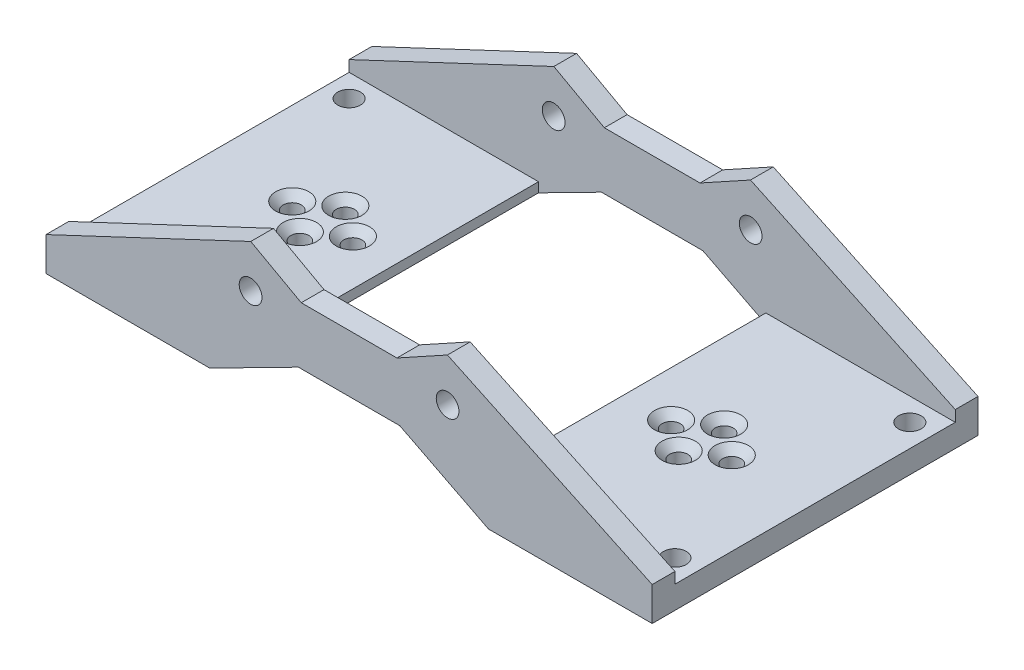
SolidWorks part; units mm, degrees
other "Markup1"
sketch "Sketch62" plane through (-128.5, -128.5, 146.8) normal (-0.0672, -0.6619, 0.7466) x (0.996, 0, 0.0896)
other "Markup2"
sketch "Sketch87" plane through (-128.5, 200.1498, -230) normal (-0.7911, 0.6051, -0.0891) x (-0.112, 0, 0.9937)
ref_plane "Front" through (0, 0, 0) normal (0, 0, 1) x (1, 0, 0)
ref_plane "Top" through (0, 0, 0) normal (0, 1, 0) x (1, 0, 0)
ref_plane "Right" through (0, 0, 0) normal (1, 0, 0) x (0, 0, -1)
sketch "Sketch1" plane through (0, 0, 0) normal (0, 0, 1) x (1, 0, 0)
  line L0 (-50.5181, 87.5) -> (0, 0) construction
  line L1 (101.0363, 0) -> (50.5181, 87.5)
  line L2 (50.5181, 87.5) -> (-50.5181, 87.5)
  line L3 (-50.5181, 87.5) -> (-101.0363, 0)
  line L4 (-101.0363, 0) -> (-50.5181, -87.5)
  line L5 (-50.5181, -87.5) -> (50.5181, -87.5)
  line L6 (50.5181, -87.5) -> (101.0363, 0)
  line L7 (0, 128.5) -> (-111.2843, 64.25) construction
  line L8 (-111.2843, 64.25) -> (-111.2843, -64.25) construction
  line L9 (-111.2843, -64.25) -> (0, -128.5) construction
  line L10 (0, -128.5) -> (111.2843, -64.25) construction
  line L11 (111.2843, -64.25) -> (111.2843, 64.25) construction
  line L12 (111.2843, 64.25) -> (0, 128.5) construction
  line L13 (0, 0) -> (50.5181, 87.5) construction
  line L14 (0, 0) -> (0, 200.1498) construction
  line L15 (-25, 93.5) -> (-25, 88.55) construction
  line L16 (-27.5, 91.1) -> (-22.5, 91.1)
  line L17 (-27.5, 91.1) -> (-27.5, 87.5)
  line L18 (-27.5, 87.5) -> (-22.5, 87.5)
  line L19 (-22.5, 91.1) -> (-22.5, 87.5)
  line L20 (-31, 93.5) -> (-19, 93.5)
  line L21 (-31, 93.5) -> (-31, 88.55)
  line L22 (-31, 88.55) -> (-19, 88.55)
  line L23 (-19, 93.5) -> (-19, 88.55)
  line L24 (48.2087, 83.5) -> (-48.2087, 83.5)
  line L25 (-48.2087, 83.5) -> (-96.4175, 0)
  line L26 (-96.4175, 0) -> (-48.2087, -83.5)
  line L27 (-48.2087, -83.5) -> (48.2087, -83.5)
  line L28 (48.2087, -83.5) -> (96.4175, 0)
  line L29 (96.4175, 0) -> (48.2087, 83.5)
  line L30 (-13, 105) -> (-13, 90) construction
  line L31 (-13, 105) -> (-0.0096, 97.5) construction
  line L32 (-11.2098, 101.4229) -> (-21.0467, 96.5)
  line L33 (-11.2098, 101.4229) -> (-7.6328, 103.2131)
  line L34 (-7.6328, 103.2131) -> (-9.4229, 106.7902)
  line L35 (-10.7973, 108.3389) -> (-23.318, 116.5991)
  line L36 (-22, 93.5) -> (-20, 93.5)
  line L37 (-22, 93.5) -> (-22, 91.5)
  line L38 (-22, 91.5) -> (-20, 91.5)
  line L39 (-20, 93.5) -> (-20, 91.5)
  line L40 (-30, 93.5) -> (-28, 93.5)
  line L41 (-30, 93.5) -> (-30, 91.5)
  line L42 (-30, 91.5) -> (-28, 91.5)
  line L43 (-28, 93.5) -> (-28, 91.5)
  line L44 (-26, 93.5) -> (-24, 93.5)
  line L45 (-26, 93.5) -> (-26, 91.5)
  line L46 (-26, 91.5) -> (-24, 91.5)
  line L47 (-24, 93.5) -> (-24, 91.5)
  line L48 (-10.7973, 108.3389) -> (-7.4584, 106.1361)
  line L49 (-7.4584, 106.1361) -> (-9.6611, 102.7973)
  line L50 (-12.9761, 110.6824) -> (-40, 97.9593)
  line L51 (-40, 97.9593) -> (-40, 93.5)
  line L52 (-40, 93.5) -> (-31, 93.5)
  line L53 (-14.7902, 108.5771) -> (-28.2041, 101.8639)
  line L54 (-40, 93.5) -> (-40, 82)
  line L55 (-40, 82) -> (-34, 72.5)
  line L56 (-34, 93.5) -> (-34, 82)
  line L57 (-34, 82) -> (-31.7895, 78.5)
  line L58 (-31.7895, 78.5) -> (-10.583, 78.5)
  line L59 (-34, 72.5) -> (-10.583, 72.5)
  line L60 (-19, 93.5) -> (-18.3926, 93.5)
  line L61 (-18.3926, 93.5) -> (-6.6883, 99.4573)
  line L62 (-6.6883, 99.4573) -> (0, 99.4573)
  line L63 (-12.9761, 110.6824) -> (-6.312, 107.0092)
  line L64 (-6.312, 107.0092) -> (0, 107.0092)
  line L65 (-6.4952, 79.25) -> (0, 75.5) construction
  line L66 (0, 75.5) -> (-8.2568, 75.5) construction
  line L67 (-9.5263, 81) -> (9.5263, 81)
  line L68 (-9.5263, 70) -> (9.5263, 70)
  line L69 (-37, 86.5) -> (-37, 97.0992) construction
  line L70 (-38.5, 93.5) -> (-35.5, 93.5) construction
  line L71 (-38.5, 93.5) -> (-38.5, 86.5) construction
  line L72 (-38.5, 86.5) -> (-35.5, 86.5) construction
  line L73 (-35.5, 93.5) -> (-35.5, 86.5) construction
  circle A0 centre (0, 0) radius 87.5 construction
  circle A1 centre (0, 0) radius 128.5 construction
  circle A2 centre (0, 128.5) radius 21 construction
  circle A3 centre (0, 128.5) radius 37.5 construction
  circle A4 centre (-13, 105) radius 1.5
  circle A5 centre (-13, 105) radius 15 construction
  circle A6 centre (-13, 105) radius 4
  arc A7 (-47.2558, 123.0415) -> (-49.9693, 122.4426) centre (-48.6061, 122.7128) ccw
  arc A8 (-47.2558, 123.0415) -> (-16.059, 109.9939) centre (-26.8516, 128.0083) ccw
  arc A9 (-49.9693, 122.4426) -> (-11.6134, 101.248) centre (-21.6463, 128.3951) ccw
  arc A10 (-14.5035, 143.6871) -> (-16.3789, 145.7376) centre (-15.4633, 144.6921) ccw
  arc A11 (-14.5035, 143.6871) -> (-10.2047, 110.1461) centre (0, 128.5) ccw
  arc A12 (-16.3789, 145.7376) -> (-15.556, 101.9232) centre (2.9376, 124.1854) ccw
  circle A13 centre (0, 75.5) radius 5
  circle A14 centre (0, 75.5) radius 3
  arc A15 (-9.5263, 81) -> (-9.5263, 70) centre (0, 75.5) ccw
  circle A16 centre (-6.4952, 79.25) radius 1.25 construction
  circle A18 centre (-6.4952, 79.25) radius 2.3 construction
  circle A19 centre (-6.4952, 71.75) radius 2.3 construction
  circle A20 centre (-6.4952, 71.75) radius 1.25 construction
  arc A21 (9.5263, 70) -> (9.5263, 81) centre (0, 75.5) ccw
  circle A22 centre (6.4952, 71.75) radius 1.25 construction
  circle A23 centre (6.4952, 79.25) radius 1.25 construction
  circle A24 centre (0, 0) radius 40.25 construction
  circle A25 centre (-8, 75.5) radius 1.75
  circle A26 centre (8, 75.5) radius 1.75
  point P29 (-25, 91.1)
  point P30 (-25, 93.5)
  point P73 (-25, 91.5)
  point P74 (-29, 91.5)
  point P75 (-21, 91.5)
  dimension "D1" = 175
  dimension "D2" = 257
  dimension "D3" = 42
  dimension "D4" = 75
  dimension "D5" = 3
  dimension "D14" = 30
  dimension "D15" = 8
  dimension "D26" = 6
  dimension "D27" = 10
  dimension "D28" = 22
  dimension "D30" = 2.5
  dimension "D31" = 4.6
  dimension "D40" = 80.5
  dimension "D41" = 3.5
  dimension "D6" = 3.6
  dimension "D7" = 6
  dimension "D8" = 12
  dimension "D9" = 5
  dimension "D10" = 4.95
  dimension "D11" = 25
  dimension "D13" = 60
  dimension "D16" = 15
  dimension "D17" = 2
  dimension "D18" = 8
  dimension "D19" = 2
  dimension "D20" = 5
  dimension "D21" = 13
  dimension "D22" = 17.5
  dimension "D23" = 60
  dimension "D24" = 19
  dimension "D25" = 40
  dimension "D29" = 7.5
  dimension "D32" = 30
  dimension "D33" = 11
  dimension "D34" = 8
  dimension "D35" = 6
  dimension "D36" = 3
  dimension "D37" = 7
  dimension "D38" = 11.5
  dimension "D39" = 6
  dimension "D42" = 16
  dimension "D12" = 4
sketch "Sketch2" plane through (0, 0, 0) normal (0, 0, 1) x (1, 0, 0)
  line L0 (-27.5, 91.1) -> (-27.5, 87.5) construction
  line L1 (-27.5, 87.5) -> (-22.5, 87.5) construction
  line L2 (-22.5, 91.1) -> (-22.5, 87.5) construction
  line L3 (-27.5, 91.1) -> (-22.5, 91.1) construction
  line L8 (-27.5, 91.1) -> (-27.5, 87.5)
  line L9 (-27.5, 87.5) -> (-22.5, 87.5)
  line L10 (-22.5, 91.1) -> (-22.5, 87.5)
  line L11 (-27.5, 91.1) -> (-22.5, 91.1)
sketch "Sketch3" plane through (0, 0, 0) normal (0, 0, 1) x (1, 0, 0)
  line L0 (-31, 93.5) -> (-19, 93.5) construction
  line L1 (-19, 93.5) -> (-19, 88.55) construction
  line L2 (-31, 88.55) -> (-19, 88.55) construction
  line L3 (-31, 93.5) -> (-31, 88.55) construction
  line L4 (-31, 93.5) -> (-19, 93.5)
  line L5 (-19, 93.5) -> (-19, 88.55)
  line L6 (-31, 88.55) -> (-19, 88.55)
  line L7 (-31, 93.5) -> (-31, 88.55)
ref_plane "Plane3" through (0, 93.5, 0) normal (0, 1, 0) x (1, 0, 0)
sketch "Sketch8" plane through (0, 93.5, 0) normal (0, 1, 0) x (1, 0, 0)
  line L0 (-32.7753, 0) -> (-19, 0) construction
  line L3 (-25, 10) -> (-25, -10) construction
  circle A0 centre (-29, 0) radius 1
  circle A1 centre (-21, 0) radius 1
  circle A2 centre (-25, 3) radius 1
  circle A3 centre (-25, -3) radius 1
  dimension "D1" = 6
  dimension "D2" = 8
  dimension "D3" = 2
sketch "Sketch6" plane through (0, 0, 0) normal (0, 0, 1) x (1, 0, 0)
  line L0 (-31, 93.5) -> (-19, 93.5) construction
  line L1 (-40, 93.5) -> (-31, 93.5) construction
  line L2 (-18.3926, 93.5) -> (-6.6883, 99.4573) construction
  line L3 (-19, 93.5) -> (-18.3926, 93.5) construction
  line L4 (-6.6883, 99.4573) -> (0, 99.4573) construction
  line L5 (-40, 97.9593) -> (-40, 93.5) construction
  line L6 (-6.312, 107.0092) -> (0, 107.0092) construction
  line L7 (-12.9761, 110.6824) -> (-6.312, 107.0092) construction
  line L8 (-12.9761, 110.6824) -> (-40, 97.9593) construction
  line L9 (-31, 93.5) -> (-19, 93.5)
  line L10 (-40, 93.5) -> (-31, 93.5)
  line L11 (-18.3926, 93.5) -> (-6.6883, 99.4573)
  line L12 (-19, 93.5) -> (-18.3926, 93.5)
  line L13 (-6.6883, 99.4573) -> (6.6883, 99.4573)
  line L14 (-40, 97.9593) -> (-40, 93.5)
  line L15 (-6.312, 107.0092) -> (6.312, 107.0092)
  line L16 (-12.9761, 110.6824) -> (-6.312, 107.0092)
  line L17 (-12.9761, 110.6824) -> (-40, 97.9593)
  line L18 (0, 0) -> (0, 200.1498) construction
  line L19 (0, 0) -> (0, 200.1498) construction
  line L20 (12.9761, 110.6824) -> (40, 97.9593)
  line L21 (12.9761, 110.6824) -> (6.312, 107.0092)
  line L22 (40, 97.9593) -> (40, 93.5)
  line L23 (19, 93.5) -> (18.3926, 93.5)
  line L24 (18.3926, 93.5) -> (6.6883, 99.4573)
  line L25 (40, 93.5) -> (31, 93.5)
  line L26 (31, 93.5) -> (19, 93.5)
  circle A0 centre (-13, 105) radius 1.5 construction
  circle A1 centre (-13, 105) radius 1.5
  circle A2 centre (13, 105) radius 1.5
extrude "Boss-Extrude4" add sketch "Sketch6" along normal mid plane 43 separate body
ref_plane "Plane2" through (0, 0, 0) normal (0, 0, 1) x (1, 0, 0)
sketch "Sketch7" plane through (0, 0, 0) normal (0, 0, 1) x (1, 0, 0)
  line L0 (40, 93.5) -> (40, 97.9593) construction
  line L1 (-40, 114.5402) -> (40, 114.5402)
  line L2 (-40, 114.5402) -> (-40, 96.5)
  line L3 (-40, 96.5) -> (40, 96.5)
  line L4 (40, 114.5402) -> (40, 96.5)
  line L5 (-40, 97.9593) -> (-40, 93.5) construction
  line L6 (0, 0) -> (0, 200.1498) construction
  line L7 (-15, 96.5) -> (15, 96.5)
  line L8 (-15, 96.5) -> (-15, 90.5)
  line L9 (-15, 90.5) -> (15, 90.5)
  line L10 (15, 96.5) -> (15, 90.5)
  line L11 (0, 0) -> (0, 200.1498) construction
  dimension "D1" = 30
  dimension "D2" = 6
extrude "Cut-Extrude3" cut sketch "Sketch7" against normal mid plane 37 contours L3 L4 L1 L2 | L8 L9 L10 L7
hole_wizard "CSK for M2 Countersunk Flat Head Screw1" positions "3DSketch3" profile "Sketch89" countersink size "M2" standard "ISO"
sketch3d "3DSketch3"
  circle A0 centre (-25, 93.5, -3) radius 1 construction
  circle A1 centre (-21, 93.5, 0) radius 1 construction
  circle A2 centre (-25, 93.5, 3) radius 1 construction
  circle A3 centre (-29, 93.5, 0) radius 1 construction
  point P3 (-25, 96.5, -3)
  point P11 (-25, 94.5, -3)
  point P12 (-21, 96.5, 0)
  point P14 (-25, 96.5, 3)
  point P16 (-29, 96.5, 0)
  point P22 (-21, 94.5, 0)
  point P26 (-25, 94.5, 3)
  point P30 (-29, 94.5, 0)
sketch "Sketch89" plane through (-25, 96.5, -3) normal (1, 0, 0) x (0, 0, 1)
  line L0 (0, 0) -> (0, 8.221)
  line L1 (0, 8.221) -> (1.2, 7.5)
  line L2 (1.2, 7.5) -> (1.2, 1)
  line L3 (1.2, 1) -> (2.2, 0)
  line L5 (2.2, 0) -> (0, 0)
  line L6 (-1.2, 1) -> (-2.2, 0) construction
  line L10 (0, 8.221) -> (-1.2, 7.5) construction
  line L11 (0, -6.35) -> (0, 107.95) construction
  dimension "Hole Dia." = 2.4
  dimension "Hole Depth" = 7.5
  dimension "Near C'Sink Dia." = 4.4
  dimension "Near C'Sink Angle" = 90
  dimension "Drill Angle" = 118
mirror "Mirror1" about plane through (0, 0, 0) normal (1, 0, 0) of "CSK for M2 Countersunk Flat Head Screw1"
sketch "Sketch90" plane through (0, 96.5, 0) normal (0, 1, 0) x (1, 0, 0)
  line L1 (37, -15.5) -> (-37, -15.5) construction
  line L2 (37, -15.5) -> (37, 15.5) construction
  line L3 (37, 15.5) -> (-37, 15.5) construction
  line L4 (-37, -15.5) -> (-37, 15.5) construction
  line L5 (37, -15.5) -> (-37, 15.5) construction
  line L6 (37, 15.5) -> (-37, -15.5) construction
  circle A0 centre (-37, 15.5) radius 1.5
  circle A1 centre (-37, -15.5) radius 1.5
  circle A2 centre (37, 15.5) radius 1.5
  circle A3 centre (37, -15.5) radius 1.5
  point P0 (0, 0)
  dimension "D1" = 3
  dimension "D2" = 74
  dimension "D3" = 31
extrude "Cut-Extrude4" cut sketch "Sketch90" against normal through all
equation "\"D39@Sketch1\"=\"D35@Sketch1\""
